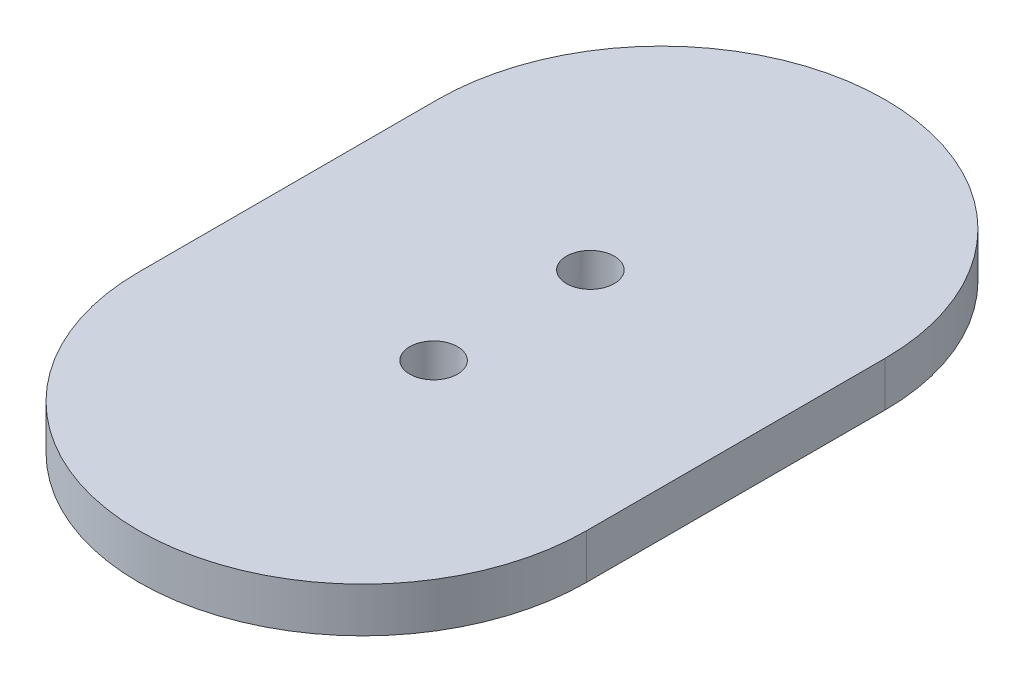
SolidWorks part; units mm, degrees
ref_plane "前视基准面" through (0, 0, 0) normal (0, 0, 1) x (1, 0, 0)
ref_plane "上视基准面" through (0, 0, 0) normal (0, 1, 0) x (1, 0, 0)
ref_plane "右视基准面" through (0, 0, 0) normal (1, 0, 0) x (0, 0, -1)
other "Configuration Table"
sketch "草图1" plane through (0, 0, 0) normal (0, 1, 0) x (1, 0, 0)
  line L0 (-15, 0) -> (-15, -20)
  line L1 (15, 0) -> (15, -20)
  arc A0 (-15, 0) -> (15, 0) centre (0, 0) cw
  arc A1 (-15, -20) -> (15, -20) centre (0, -20) ccw
  point P5 (27.6695, -0.054)
  point P7 (16.9924, -13.6498)
  dimension "D1" = 30
  dimension "D2" = 20
extrude "凸台-拉伸1" add sketch "草图1" along normal blind 3
sketch "草图2" plane through (0, 3, 0) normal (0, 1, 0) x (1, 0, 0)
  line L0 (0, 0) -> (0, -38.1515) construction
  line L1 (-15, -10) -> (20.6265, -10) construction
  line L2 (-15, 0) -> (-15, -20) construction
  circle A0 centre (0, -4.75) radius 1.6
  circle A1 centre (0, -15.25) radius 1.6
  point P7 (0, 0)
  point P12 (0, -15.5397)
  point P13 (0, 0)
  dimension "D1" = 3.2
  dimension "D2" = 3.2
  dimension "D4" = 5.25
  dimension "D3" = 10.5
extrude "切除-拉伸1" cut sketch "草图2" against normal up to surface (3 mm away) up to face at (0, 0, 10)
